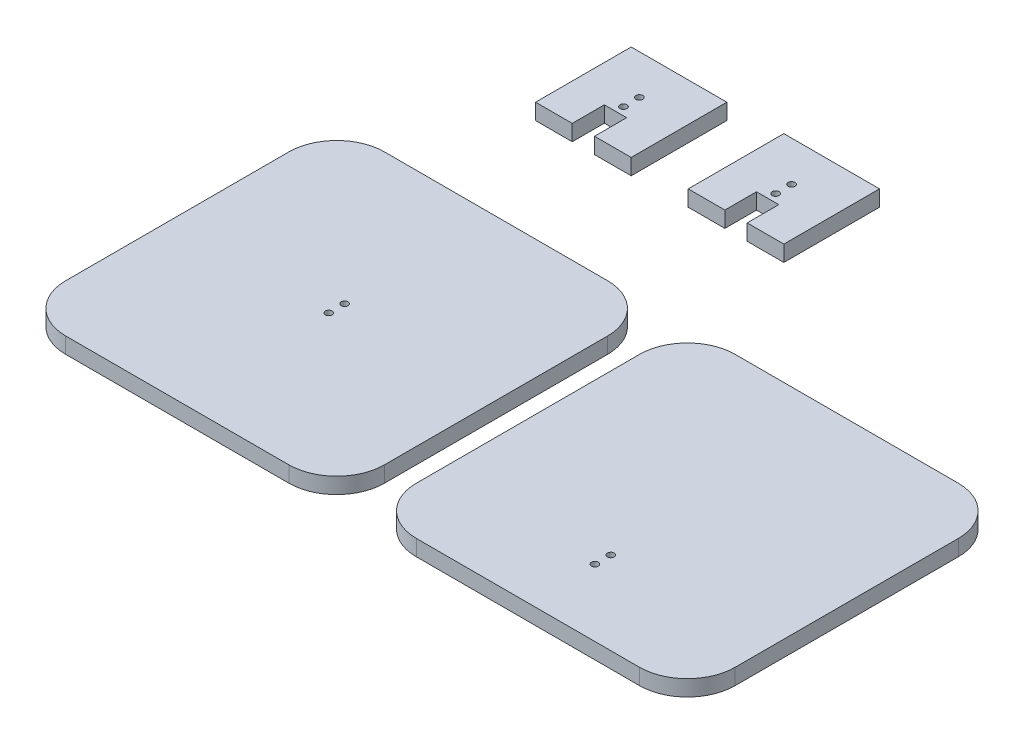
SolidWorks part; units mm, degrees
ref_plane "Front Plane" through (0, 0, 0) normal (0, 0, 1) x (1, 0, 0)
ref_plane "Top Plane" through (0, 0, 0) normal (0, 1, 0) x (1, 0, 0)
ref_plane "Right Plane" through (0, 0, 0) normal (1, 0, 0) x (0, 0, -1)
sketch "Sketch1" plane through (0, 0, 0) normal (0, 1, 0) x (1, 0, 0)
  line L1 (0, 0) -> (200, 0)
  line L2 (0, 0) -> (0, 200)
  line L3 (0, 200) -> (200, 200)
  line L4 (200, 0) -> (200, 200)
  line L5 (220, 200) -> (420, 200)
  line L6 (220, 200) -> (220, 0)
  line L7 (220, 0) -> (420, 0)
  line L8 (420, 200) -> (420, 0)
  dimension "D1" = 200
  dimension "D2" = 200
  dimension "D3" = 200
  dimension "D4" = 200
  dimension "D5" = 20
  dimension "D6" = 0
extrude "Boss-Extrude1" add sketch "Sketch1" along normal blind 10
fillet "Fillet1" radius 30 4 edges at (0, 5, -200) (0, 5, 0) (200, 5, 0) (200, 5, -200)
fillet "Fillet2" radius 30 4 edges at (220, 5, -200) (220, 5, 0) (420, 5, -200) (420, 5, 0)
sketch "Sketch2" plane through (0, 10, 0) normal (0, 1, 0) x (1, 0, 0)
  line L0 (100, 200) -> (100, 0) construction
  line L1 (170, 200) -> (30, 200) construction
  line L2 (30, 0) -> (170, 0) construction
  line L3 (0, 100) -> (200, 100) construction
  line L4 (0, 170) -> (0, 30) construction
  line L5 (200, 30) -> (200, 170) construction
  circle A0 centre (100, 105) radius 2.15
  circle A1 centre (100, 95) radius 2.15
  dimension "D1" = 4.3
  dimension "D2" = 4.3
  dimension "D3" = 5
  dimension "D4" = 5
extrude "Cut-Extrude1" cut sketch "Sketch2" against normal blind 15
sketch "Sketch3" plane through (0, 10, 0) normal (0, 1, 0) x (1, 0, 0)
  line L0 (320, 200) -> (320, 0) construction
  line L1 (390, 200) -> (250, 200) construction
  line L2 (250, 0) -> (390, 0) construction
  line L3 (320, 0) -> (428.0676, -17.633) construction
  line L4 (428.0676, -17.633) -> (428.0676, -18.4213) construction
  line L5 (220, 100) -> (420, 100) construction
  line L6 (220, 170) -> (220, 30) construction
  line L7 (420, 30) -> (420, 170) construction
  circle A0 centre (320, 52) radius 2.15
  circle A1 centre (320, 42) radius 2.15
  point P18 (320, 95)
  point P19 (320, 100)
  dimension "D1" = 4.3
  dimension "D2" = 4.3
  dimension "D3" = 10
  dimension "D4" = 5
  dimension "D5" = 43
extrude "Cut-Extrude2" cut sketch "Sketch3" against normal blind 15
sketch "Sketch4" plane through (0, 0, 0) normal (0, 1, 0) x (1, 0, 0)
  line L0 (80.383, 334.3955) -> (80.383, 274.3955) construction
  line L1 (50.383, 334.3955) -> (110.383, 334.3955)
  line L2 (50.383, 334.3955) -> (50.383, 274.3955)
  line L3 (50.383, 274.3955) -> (73.383, 274.3955)
  line L4 (110.383, 334.3955) -> (110.383, 274.3955)
  line L5 (145.3476, 335.196) -> (205.3476, 335.196)
  line L6 (145.3476, 335.196) -> (145.3476, 275.196)
  line L7 (145.3476, 275.196) -> (168.3476, 275.196)
  line L8 (205.3476, 335.196) -> (205.3476, 275.196)
  line L9 (50.383, 304.3955) -> (205.3476, 305.196) construction
  line L10 (175.3476, 335.196) -> (175.3476, 275.196) construction
  line L11 (87.383, 274.3955) -> (110.383, 274.3955)
  line L13 (73.383, 274.3955) -> (73.383, 294.5504)
  line L14 (73.383, 294.5504) -> (87.383, 294.5504)
  line L15 (87.383, 274.3955) -> (87.383, 294.5504)
  line L17 (168.3476, 275.196) -> (168.3476, 295.041)
  line L18 (168.3476, 295.041) -> (182.3476, 295.041)
  line L19 (182.3476, 275.196) -> (182.3476, 295.041)
  line L20 (182.3476, 275.196) -> (205.3476, 275.196)
  circle A0 centre (80.383, 309.5506) radius 2.15
  circle A1 centre (80.383, 299.5504) radius 2.15
  circle A2 centre (175.3476, 310.0411) radius 2.15
  circle A3 centre (175.3476, 300.041) radius 2.15
  dimension "D5" = 4.3
  dimension "D6" = 4.3
  dimension "D9" = 4.3
  dimension "D10" = 4.3
  dimension "D1" = 60
  dimension "D2" = 60
  dimension "D3" = 60
  dimension "D4" = 60
  dimension "D7" = 5
  dimension "D8" = 5
  dimension "D11" = 5
  dimension "D12" = 5
  dimension "D13" = 7
  dimension "D14" = 7
  dimension "D15" = 7
  dimension "D16" = 7
  dimension "D17" = 5
  dimension "D18" = 5
extrude "Boss-Extrude2" add sketch "Sketch4" along normal blind 10 separate body
